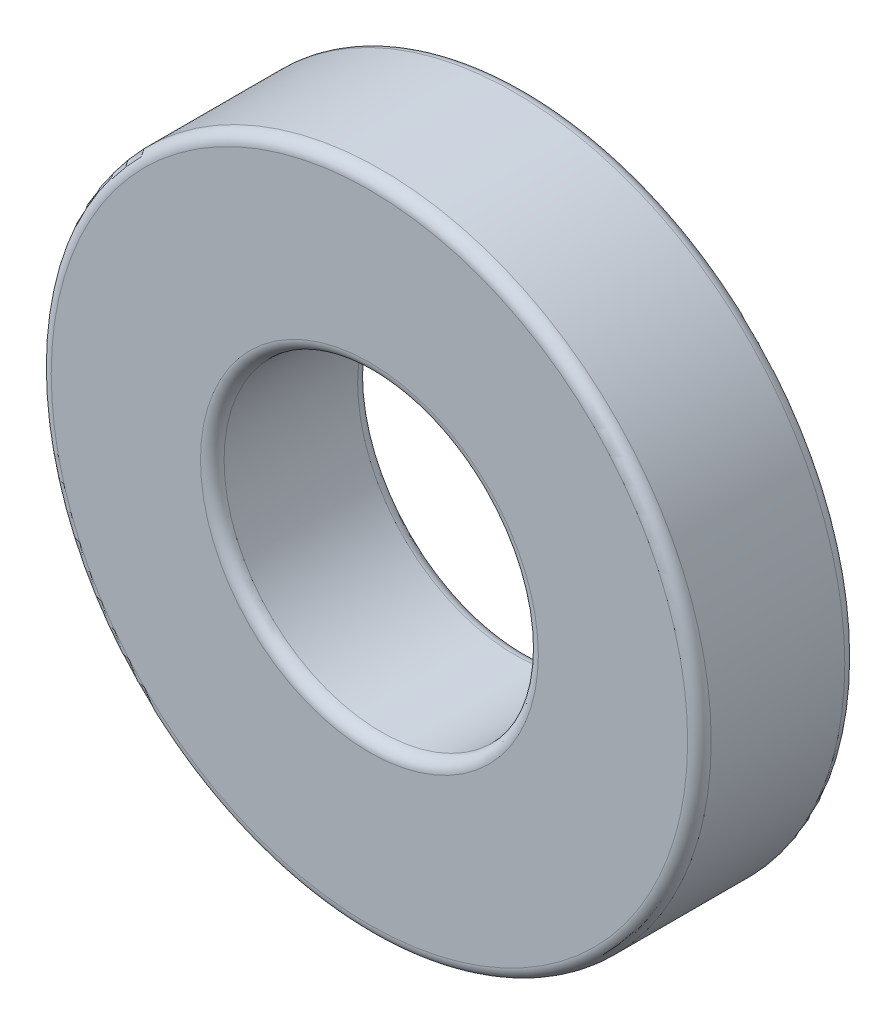
SolidWorks part; units mm, degrees
ref_plane "Plan de face" through (0, 0, 0) normal (0, 0, 1) x (1, 0, 0)
ref_plane "Plan de dessus" through (0, 0, 0) normal (0, 1, 0) x (1, 0, 0)
ref_plane "Plan de droite" through (0, 0, 0) normal (1, 0, 0) x (0, 0, -1)
sketch "Esquisse1" plane through (0, 0, 0) normal (0, 0, 1) x (1, 0, 0)
  circle A0 centre (0, 0) radius 10
  circle A1 centre (0, 0) radius 21
  dimension "D1" = 42
  dimension "D2" = 20
extrude "Boss.-Extru.1" add sketch "Esquisse1" along normal blind 10
fillet "Congé1" radius 0.75 4 edges at (10, 0, 10) (21, 0, 10) (10, 0, 0) (21, 0, 0)
